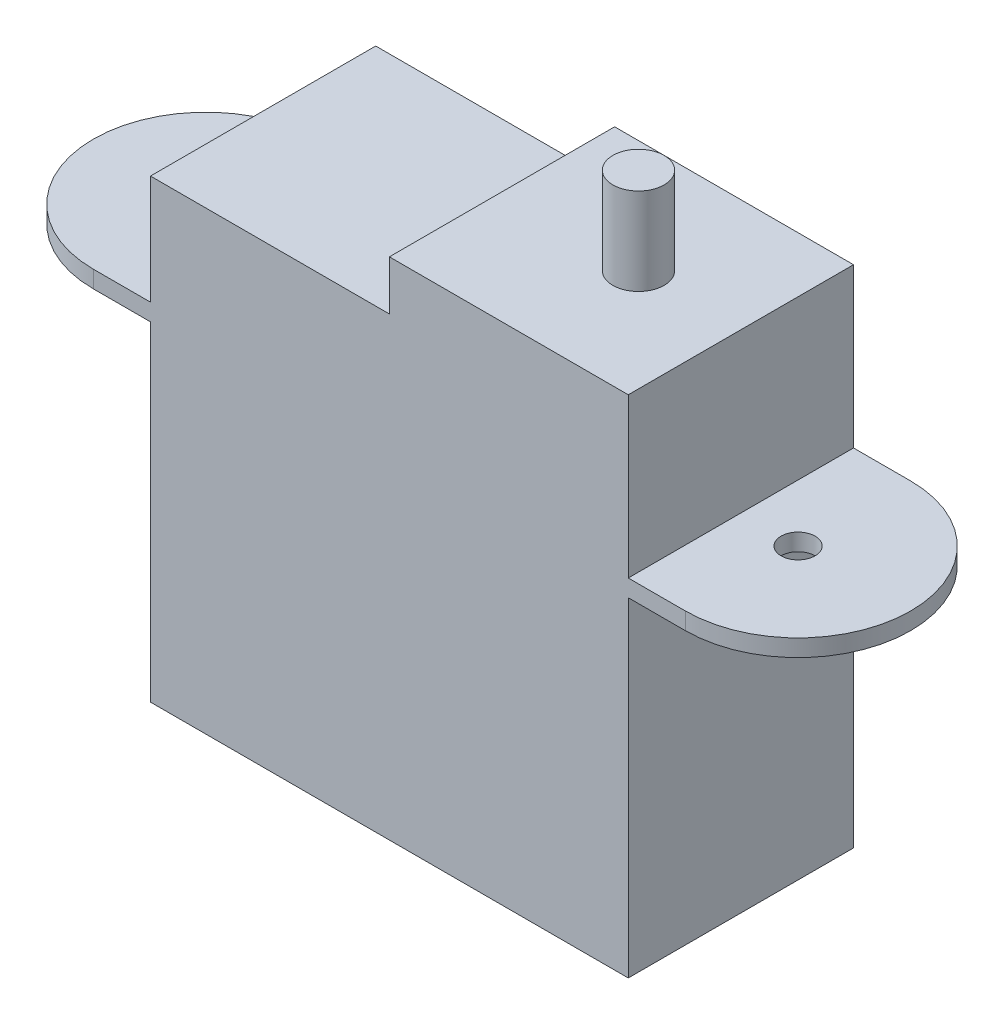
SolidWorks part; units mm, degrees
ref_plane "Front Plane" through (0, 0, 0) normal (0, 0, 1) x (1, 0, 0)
ref_plane "Top Plane" through (0, 0, 0) normal (0, 1, 0) x (1, 0, 0)
ref_plane "Right Plane" through (0, 0, 0) normal (1, 0, 0) x (0, 0, -1)
sketch "Sketch1" plane through (0, 0, 0) normal (0, 1, 0) x (1, 0, 0)
  line L1 (0, 0) -> (28, 0)
  line L2 (0, 0) -> (0, 13.2)
  line L3 (0, 13.2) -> (28, 13.2)
  line L4 (28, 0) -> (28, 13.2)
  dimension "D1" = 28
  dimension "D2" = 13.2
extrude "Boss-Extrude1" add sketch "Sketch1" along normal blind 19.3
sketch "Sketch2" plane through (0, 19.3, 0) normal (0, 1, 0) x (1, 0, 0)
  line L0 (-3.35, 6.6) -> (31.35, 6.6) construction
  line L1 (-3.35, 13.2) -> (31.35, 13.2)
  line L2 (-3.35, 0) -> (31.35, 0)
  line L3 (28, 13.2) -> (0, 13.2) construction
  line L4 (0, 0) -> (28, 0) construction
  arc A0 (-3.35, 13.2) -> (-3.35, 0) centre (-3.35, 6.6) ccw
  arc A1 (31.35, 0) -> (31.35, 13.2) centre (31.35, 6.6) ccw
  point P2 (14, 6.6)
  point P11 (0, 0)
  point P12 (14, 0)
  point P13 (-4.6476, 4.25)
  point P14 (14, 0)
  dimension "D1" = 34.7
extrude "Boss-Extrude2" add sketch "Sketch2" along normal blind 1
sketch "Sketch3" plane through (0, 20.3, 0) normal (0, 1, 0) x (1, 0, 0)
  line L0 (31.35, 13.2) -> (-3.35, 13.2) construction
  line L1 (0, 0) -> (28, 0)
  line L2 (0, 0) -> (0, 13.2)
  line L3 (0, 13.2) -> (28, 13.2)
  line L4 (28, 0) -> (28, 13.2)
  dimension "D1" = 28
extrude "Boss-Extrude3" add sketch "Sketch3" along normal offset from surface (9.3 mm away) 29.6 up to face at (14, 0, -6.6)
sketch "Sketch4" plane through (0, 0, 0) normal (0, 0, 1) x (1, 0, 0)
  line L0 (0, 26.7) -> (7, 26.7)
  line L2 (7, 26.7) -> (14, 26.7)
  line L3 (14, 26.7) -> (14, 29.6)
  line L4 (28, 29.6) -> (0, 29.6) construction
  line L5 (14, 29.6) -> (28, 29.6)
  line L6 (28, 29.6) -> (28, 24.95)
  line L7 (28, 29.6) -> (28, 20.3) construction
  line L8 (28, 24.95) -> (30, 24.95)
  line L9 (30, 24.95) -> (30, 31.6)
  line L10 (30, 31.6) -> (0, 31.6)
  line L11 (0, 31.6) -> (0, 26.7)
  line L12 (0, 29.6) -> (0, 20.3) construction
  line L15 (0, 0) -> (28, 0) construction
  point P2 (0, 16.6364)
  dimension "D2" = 26.7
  dimension "D3" = 7
  dimension "D4" = 7
  dimension "D5" = 30
  dimension "D6" = 2
extrude "Cut-Extrude1" cut sketch "Sketch4" against normal blind 20.2
sketch "Sketch5" plane through (0, 20.3, 0) normal (0, 1, 0) x (1, 0, 0)
  circle A0 centre (-3.35, 6.6) radius 1
  circle A1 centre (31.35, 6.6) radius 1
  dimension "D1" = 2
  dimension "D2" = 2
extrude "Cut-Extrude2" cut sketch "Sketch5" against normal through all
sketch "Sketch6" plane through (0, 29.6, 0) normal (0, 1, 0) x (1, 0, 0)
  line L0 (0, 0) -> (0, 13.2) construction
  line L1 (28, 13.2) -> (28, 0) construction
  circle A0 centre (22, 6.6) radius 1.5
  point P4 (0, 0)
  point P7 (28, 6.6)
  dimension "D2" = 3
  dimension "D1" = 22
extrude "Boss-Extrude4" add sketch "Sketch6" along normal offset from surface (5.1 mm away) 34.7 up to face at (14, 0, -6.6)
